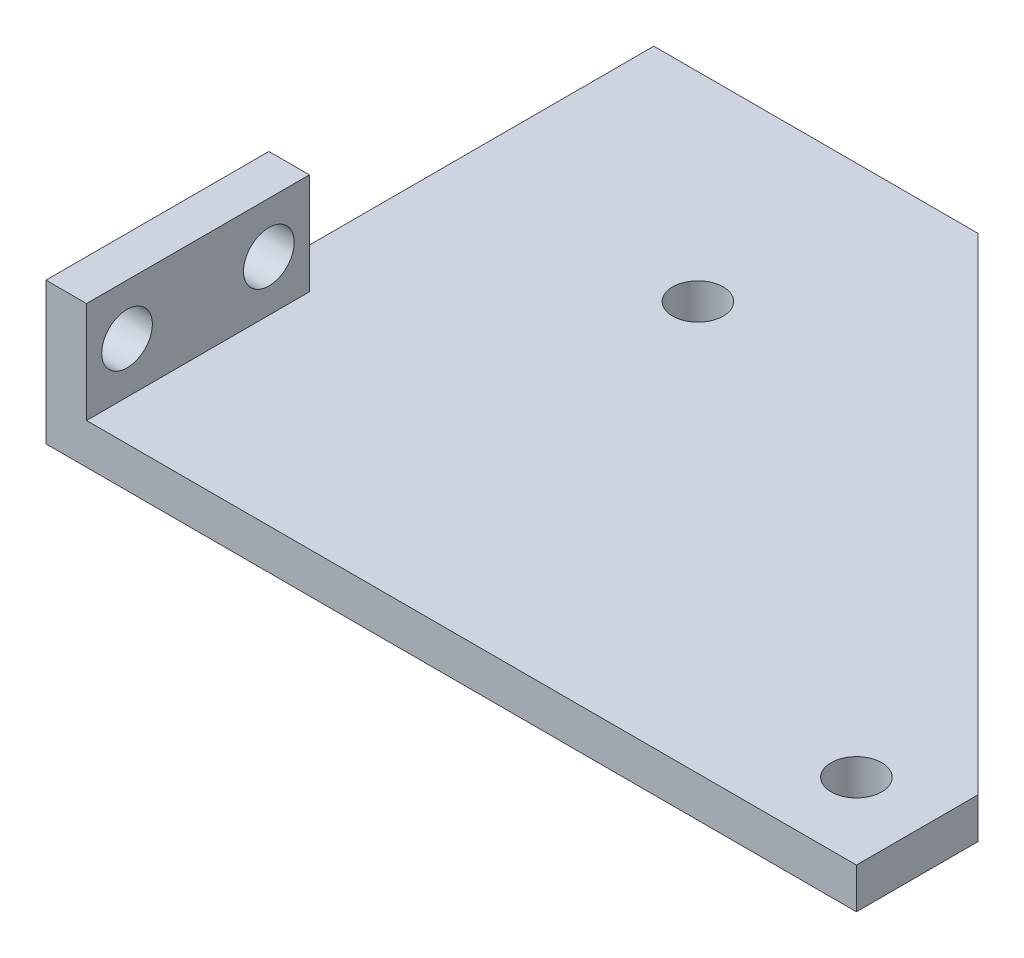
SolidWorks part; units mm, degrees
ref_plane "Front Plane" through (0, 0, 0) normal (0, 0, 1) x (1, 0, 0)
ref_plane "Top Plane" through (0, 0, 0) normal (0, 1, 0) x (1, 0, 0)
ref_plane "Right Plane" through (0, 0, 0) normal (1, 0, 0) x (0, 0, -1)
sketch "Sketch1" plane through (0, 0, 0) normal (0, 1, 0) x (1, 0, 0)
  line L0 (32, 60) -> (80, 12)
  line L1 (0, 0) -> (80, 0)
  line L2 (0, 0) -> (0, 60)
  line L5 (32, 60) -> (0, 60)
  line L6 (80, 0) -> (80, 12)
  circle A0 centre (24, 40.35) radius 2.5
  circle A1 centre (72.5, 7.5) radius 2.5
  point P1 (0, 0)
  dimension "D4" = 5
  dimension "D5" = 5
  dimension "D2" = 32.85
  dimension "D3" = 48.5
  dimension "D6" = 60
  dimension "D7" = 7.5
  dimension "D14" = 7.5
  dimension "D15" = 12
  dimension "D16" = 32
  dimension "D17" = 80
extrude "Boss-Extrude1" add sketch "Sketch1" along normal blind 4
sketch "Sketch2" plane through (0, 4, 0) normal (0, 1, 0) x (1, 0, 0)
  line L1 (0, 0) -> (4, 0)
  line L2 (0, 0) -> (0, 22)
  line L3 (0, 22) -> (4, 22)
  line L4 (4, 0) -> (4, 22)
  dimension "D1" = 4
  dimension "D2" = 22
extrude "Boss-Extrude2" add sketch "Sketch2" along normal blind 10
sketch "Sketch3" plane through (0, 0, 0) normal (-1, 0, 0) x (0, 0, 1)
  line L0 (0, 14) -> (0, 0) construction
  line L1 (-22, 14) -> (0, 14) construction
  circle A0 centre (-18, 9) radius 2.5
  circle A1 centre (-4, 9) radius 2.5
  dimension "D1" = 5
  dimension "D2" = 5
  dimension "D3" = 14
  dimension "D4" = 4
  dimension "D5" = 0
  dimension "D6" = 5
extrude "Cut-Extrude1" cut sketch "Sketch3" against normal blind 20
